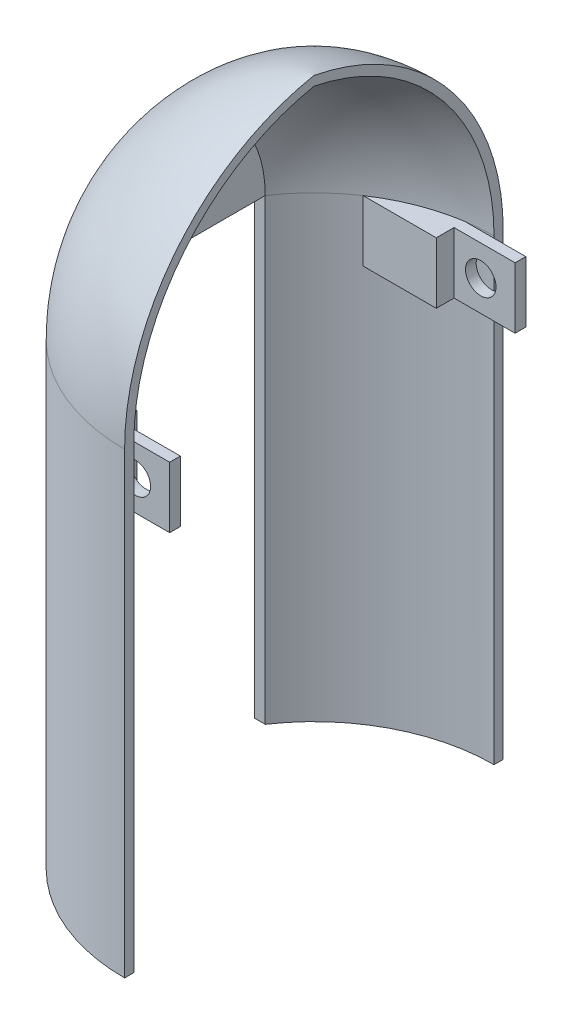
SolidWorks part; units mm, degrees
ref_plane "Front Plane" through (0, 0, 0) normal (0, 0, 1) x (1, 0, 0)
ref_plane "Top Plane" through (0, 0, 0) normal (0, 1, 0) x (1, 0, 0)
ref_plane "Right Plane" through (0, 0, 0) normal (1, 0, 0) x (0, 0, -1)
sketch "Sketch1" plane through (0, 0, 0) normal (0, 0, 1) x (1, 0, 0)
  line L0 (62, 0) -> (59, 0)
  line L2 (0, 75) -> (0, 71.9432)
  arc A0 (62, 0) -> (0, 75) centre (-14.3629, 0) ccw
  arc A1 (59, 0) -> (0, 71.9432) centre (-14.3629, 0) ccw
  arc A2 (59, 0) -> (-0.5643, 72.0535) centre (-14.3629, 0) ccw construction
  dimension "D1" = 3
  dimension "D2" = 62
  dimension "D3" = 75
revolve "Revolve1" add sketch "Sketch1" angle 360 about L2
sketch "Sketch2" plane through (0, 0, 0) normal (0, -1, 0) x (-1, 0, 0)
  line L1 (52.5, 72.8837) -> (-52.5, 72.8837)
  line L2 (52.5, 72.8837) -> (52.5, -72.8837)
  line L3 (52.5, -72.8837) -> (-52.5, -72.8837)
  line L4 (-52.5, 72.8837) -> (-52.5, -72.8837)
  line L5 (52.5, 72.8837) -> (-52.5, -72.8837) construction
  line L6 (52.5, -72.8837) -> (-52.5, 72.8837) construction
  point P0 (0, 0)
  dimension "D1" = 105
  dimension "D2" = 145.7674
extrude "Cut-Extrude2" cut sketch "Sketch2" against normal through all flip side to cut
sketch "Sketch3" plane through (0, 0, 0) normal (0, -1, 0) x (1, 0, 0)
  line L0 (-52.5, 32.9811) -> (-48.9209, 32.9811)
  line L1 (-48.9209, 32.9811) -> (-48.9209, -32.9811)
  line L2 (-48.9209, -32.9811) -> (-52.5, -32.9811)
  line L3 (-52.5, -32.9811) -> (-52.5, 32.9811)
  line L4 (0, 0) -> (0, 17.4115) construction
  line L5 (48.9209, -32.9811) -> (52.5, -32.9811)
  line L6 (52.5, 32.9811) -> (48.9209, 32.9811)
  line L7 (52.5, -32.9811) -> (52.5, 32.9811)
  line L8 (48.9209, 32.9811) -> (48.9209, -32.9811)
  arc A0 (52.5, 26.9212) -> (-52.5, 26.9212) centre (0, 0) ccw construction
  arc A1 (-52.5, -26.9212) -> (52.5, -26.9212) centre (0, 0) ccw construction
extrude "Boss-Extrude2" add sketch "Sketch3" against normal up to surface
sketch "Sketch4" plane through (0, 0, 0) normal (0, -1, 0) x (-1, 0, 0)
  line L0 (52.5007, -32.98) -> (48.9216, -32.98)
  line L2 (-48.9216, -32.98) -> (-52.5007, -32.98)
  line L3 (0, 0) -> (-30.1101, 0) construction
  line L5 (-48.9216, 32.98) -> (-52.5007, 32.98)
  line L6 (52.5007, 32.98) -> (48.9216, 32.98)
  arc A1 (-48.9216, -32.98) -> (48.9216, -32.98) centre (0, 0) ccw
  arc A2 (-52.5007, -32.98) -> (52.5007, -32.98) centre (0, 0) ccw
  arc A3 (-49.9603, -31.3842) -> (49.9603, -31.3842) centre (0, 0) ccw construction
  arc A4 (-52.5007, 32.98) -> (52.5007, 32.98) centre (0, 0) cw
  arc A5 (-48.9216, 32.98) -> (48.9216, 32.98) centre (0, 0) cw
  dimension "D2" = 62
  dimension "D3" = 32.98
  dimension "D1" = 3
extrude "Boss-Extrude4" add sketch "Sketch4" along normal blind 150
sketch "Sketch5" plane through (0, 0, 0) normal (0, 0, 1) x (1, 0, 0)
  line L1 (0, 81.3691) -> (89.0394, 81.3691)
  line L2 (0, 81.3691) -> (0, -154.2705)
  line L3 (0, -154.2705) -> (89.0394, -154.2705)
  line L4 (89.0394, 81.3691) -> (89.0394, -154.2705)
extrude "Cut-Extrude3" cut sketch "Sketch5" against normal through all both and the other way through all
sketch "Sketch6" plane through (-52.5, 0, 0) normal (-1, 0, 0) x (0, 0, 1)
  line L0 (0, 0) -> (0, 19.7166) construction
  line L1 (-32.98, 0) -> (32.98, 0) construction
  circle A0 centre (-5, 10) radius 1.8
  circle A1 centre (5, 10) radius 1.8
  dimension "D1" = 3.6
  dimension "D2" = 10
  dimension "D3" = 10
extrude "Cut-Extrude4" cut sketch "Sketch6" against normal through all
ref_plane "Plane2" through (-8.9209, 0, 0) normal (1, 0, 0) x (0, 0, -1)
sketch "Sketch8" plane through (-8.9209, 0, 0) normal (1, 0, 0) x (0, 0, -1)
  line L0 (59, 0) -> (49, 0)
  line L1 (59, 0) -> (32.9811, 0) construction
  line L2 (49, 0) -> (49, -20)
  line L3 (49, -20) -> (59, -20)
  line L4 (59, -150) -> (59, 0) construction
  line L5 (59, -20) -> (59, 0)
  line L6 (0, 0) -> (0, -38.146) construction
  line L7 (-49, -20) -> (-59, -20)
  line L8 (-49, 0) -> (-49, -20)
  line L9 (-59, 0) -> (-49, 0)
  line L10 (-59, -20) -> (-59, 0)
  dimension "D1" = 20
  dimension "D2" = 10
extrude "Boss-Extrude5" add sketch "Sketch8" against normal up to surface (23.9425 mm away)
sketch "Sketch9" plane through (-8.9209, 0, 0) normal (1, 0, 0) x (0, 0, -1)
  line L0 (58.3217, 0) -> (49, 0) construction
  line L1 (54.8217, 0) -> (58.3217, 0)
  line L2 (54.8217, 0) -> (54.8217, -20)
  line L3 (54.8217, -20) -> (58.3217, -20)
  line L4 (58.3217, 0) -> (58.3217, -20)
  line L5 (49, -20) -> (58.3217, -20) construction
  line L7 (0, 0) -> (0, -29.7251) construction
  line L8 (-54.8217, -20) -> (-58.3217, -20)
  line L9 (-58.3217, 0) -> (-58.3217, -20)
  line L10 (-54.8217, 0) -> (-58.3217, 0)
  line L11 (-54.8217, 0) -> (-54.8217, -20)
  line L12 (58.3217, -20) -> (58.3217, 0) construction
  dimension "D1" = 3.5
extrude "Boss-Extrude6" add sketch "Sketch9" along normal blind 20
sketch "Sketch10" plane through (0, 0, 58.3217) normal (0, 0, 1) x (1, 0, 0)
  line L0 (11.0791, 0) -> (-8.9209, 0) construction
  line L1 (11.0791, 0) -> (11.0791, -20) construction
  circle A0 centre (-0.1709, -10) radius 5
  dimension "D1" = 10
  dimension "D2" = 10
  dimension "D3" = 11.25
extrude "Cut-Extrude5" cut sketch "Sketch10" against normal up to surface (116.6434 mm away) up to face at (1.0791, -10, -58.3217)
